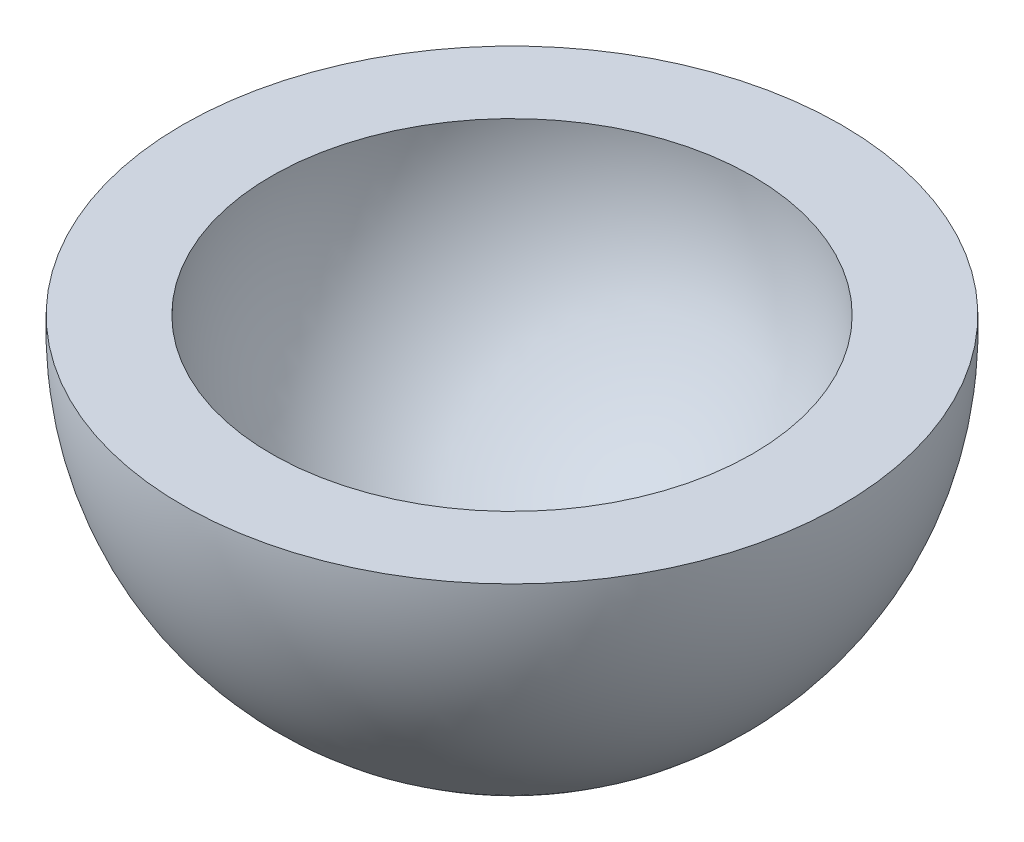
SolidWorks part; units mm, degrees
ref_plane "Front Plane" through (0, 0, 0) normal (0, 0, 1) x (1, 0, 0)
ref_plane "Top Plane" through (0, 0, 0) normal (0, 1, 0) x (1, 0, 0)
ref_plane "Right Plane" through (0, 0, 0) normal (1, 0, 0) x (0, 0, -1)
sketch "Sketch1" plane through (0, 0, 0) normal (0, 0, 1) x (1, 0, 0)
  line L0 (200, 0) -> (250, 0)
  line L1 (0, -250) -> (0, 0) construction
  arc A0 (0, -200) -> (200, 0) centre (0, 0) ccw
  arc A1 (0, -250) -> (250, 0) centre (0, 0) ccw
  point P6 (0, 0)
  point P7 (0, -200)
  dimension "D1" = 200
  dimension "D2" = 50
revolve "Revolve-Thin1" add sketch "Sketch1" angle 360 about L1 wall 10
